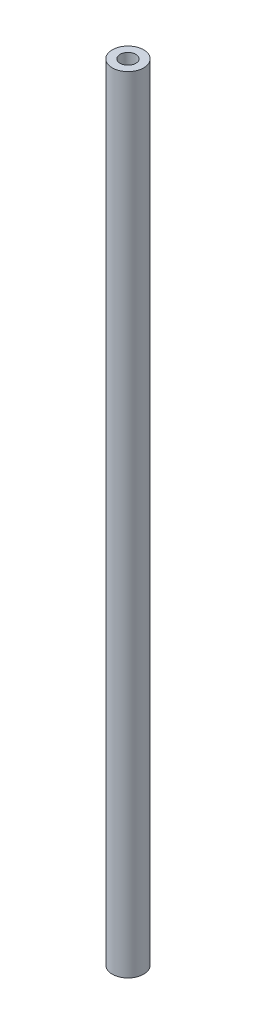
SolidWorks part; units mm, degrees
ref_plane "前视基准面" through (0, 0, 0) normal (0, 0, 1) x (1, 0, 0)
ref_plane "上视基准面" through (0, 0, 0) normal (0, 1, 0) x (1, 0, 0)
ref_plane "右视基准面" through (0, 0, 0) normal (1, 0, 0) x (0, 0, -1)
other "Configuration Table"
sketch "草图1" plane through (0, 0, 0) normal (0, 1, 0) x (1, 0, 0)
  circle A0 centre (0, 0) radius 3
  dimension "D1" = 6
extrude "凸台-拉伸1" add sketch "草图1" along normal blind 150
sketch "草图2" plane through (0, 150, 0) normal (0, 1, 0) x (1, 0, 0)
  circle A0 centre (0, 0) radius 1.5
  dimension "D1" = 3
extrude "切除-拉伸1" cut sketch "草图2" against normal blind 10
sketch "草图3" plane through (0, 0, 0) normal (0, -1, 0) x (1, 0, 0)
  circle A0 centre (0, 0) radius 1.5
  dimension "D1" = 3
extrude "切除-拉伸2" cut sketch "草图3" against normal blind 10
